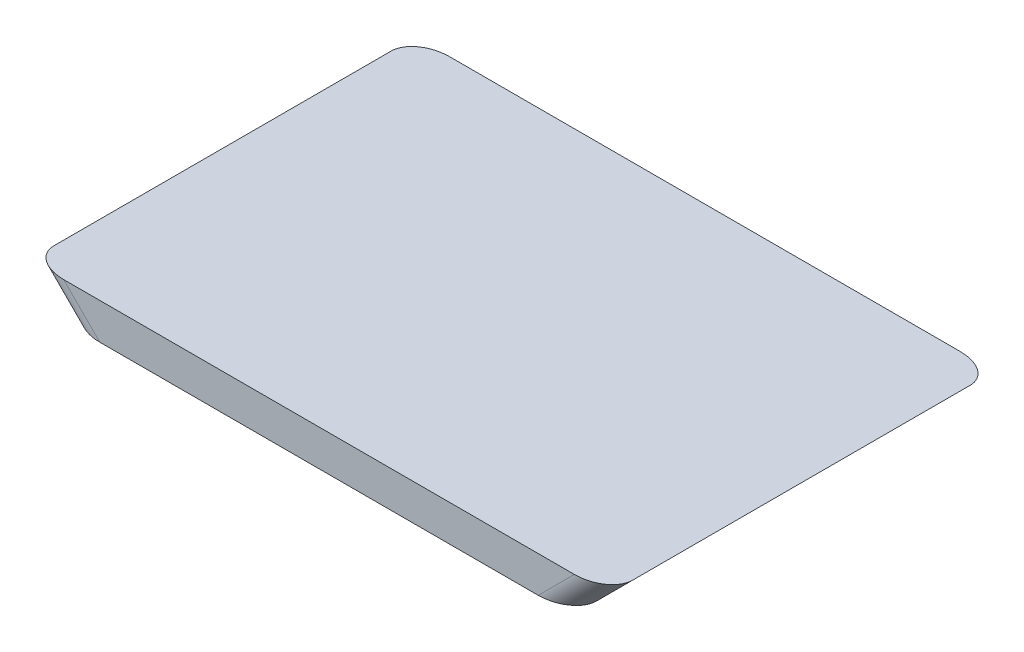
SolidWorks part; units mm, degrees
material "POLYURETHANE (11671)"
ref_plane "Front Plane" through (0, 0, 0) normal (0, 0, 1) x (1, 0, 0)
ref_plane "Top Plane" through (0, 0, 0) normal (0, 1, 0) x (1, 0, 0)
ref_plane "Right Plane" through (0, 0, 0) normal (1, 0, 0) x (0, 0, -1)
sketch "Sketch1" plane through (0, 0, 0) normal (0, 0, 1) x (1, 0, 0)
  line L0 (-38.1, 2.3813) -> (38.1, 2.3813)
  line L3 (-33.3375, -2.3813) -> (33.3375, -2.3813)
  line L5 (-38.1, 2.3813) -> (-33.3375, -2.3813)
  line L6 (38.1, 2.3813) -> (33.3375, -2.3813)
  dimension "D1" = 38.1
  dimension "D2" = 2.3813
  dimension "D3" = 6.7352
  dimension "D4" = 6.7352
  dimension "D5" = 66.675
  dimension "D6" = 4.7625
extrude "Boss-Extrude1" add sketch "Sketch1" along normal blind 50.8
fillet "Fillet1" radius 3.175 4 edges at (35.7187, 0, 50.8) (-35.7188, 0, 50.8) (-35.7188, 0, 0) (35.7187, 0, 0)
